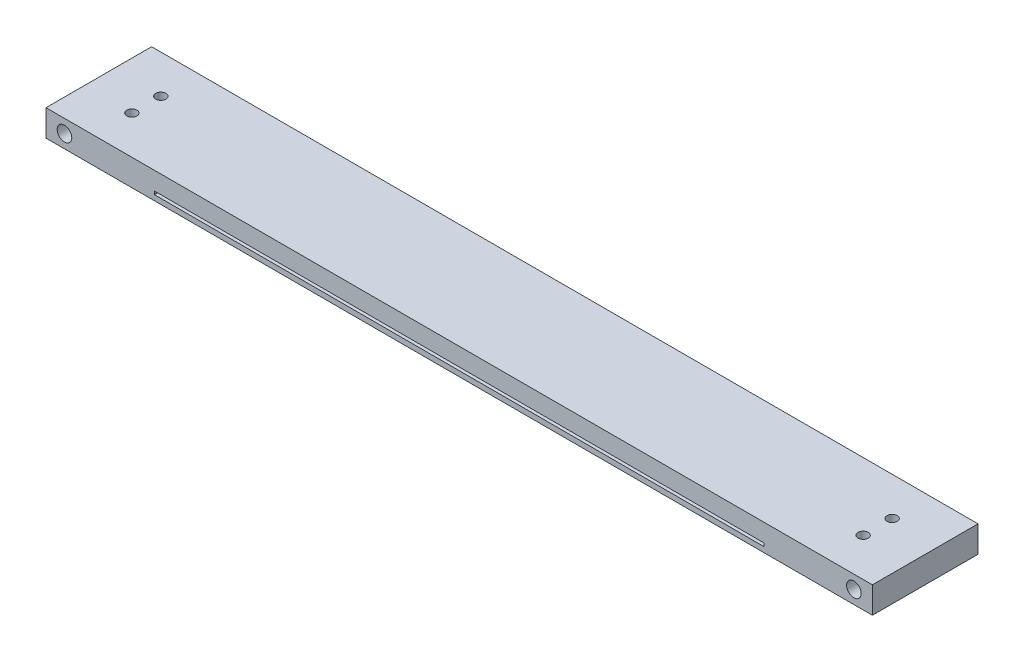
SolidWorks part; units mm, degrees
ref_plane "Front Plane" through (0, 0, 0) normal (0, 0, 1) x (1, 0, 0)
ref_plane "Top Plane" through (0, 0, 0) normal (0, 1, 0) x (1, 0, 0)
ref_plane "Right Plane" through (0, 0, 0) normal (1, 0, 0) x (0, 0, -1)
sketch "Sketch1" plane through (0, 0, 0) normal (1, 0, 0) x (0, 0, -1)
  line L1 (0, 0) -> (40, 0)
  line L2 (0, 0) -> (0, 10)
  line L3 (0, 10) -> (40, 10)
  line L4 (40, 0) -> (40, 10)
  dimension "D1" = 10
  dimension "D2" = 40
extrude "Boss-Extrude1" add sketch "Sketch1" along normal blind 312.998
sketch "Sketch2" plane through (0, 0, -40) normal (0, 0, -1) x (-1, 0, 0)
  line L1 (-271.949, 2) -> (-41.049, 2)
  line L2 (-271.949, 2) -> (-271.949, 3.2)
  line L3 (-271.949, 3.2) -> (-41.049, 3.2)
  line L4 (-41.049, 2) -> (-41.049, 3.2)
  line L5 (-271.949, 3.2) -> (-312.998, 0) construction
  line L6 (-41.049, 3.2) -> (0, 0) construction
  line L7 (-312.998, 0) -> (0, 0) construction
  dimension "D1" = 230.9
  dimension "D2" = 2
  dimension "D3" = 1.2
extrude "Cut-Extrude1" cut sketch "Sketch2" against normal through all
sketch "Sketch3" plane through (0, 10, 0) normal (0, 1, 0) x (1, 0, 0)
  line L0 (156.499, 71.4665) -> (156.499, -49.9307) construction
  line L1 (0, 40) -> (156.499, 71.4665) construction
  line L2 (156.499, 71.4665) -> (312.998, 40) construction
  line L3 (312.998, 40) -> (312.998, 0) construction
  line L4 (312.998, 40) -> (0, 40) construction
  line L5 (312.998, 40) -> (294.998, 25.5) construction
  line L6 (294.998, 25.5) -> (294.998, 14.5) construction
  line L7 (294.998, 14.5) -> (312.998, 0) construction
  circle A0 centre (294.998, 25.5) radius 1.9177
  circle A1 centre (294.998, 14.5) radius 1.9177
  circle A2 centre (18, 14.5) radius 1.9177
  circle A3 centre (18, 25.5) radius 1.9177
  dimension "D3" = 3.8354
  dimension "D1" = 18
  dimension "D2" = 14.5
extrude "Cut-Extrude2" cut sketch "Sketch3" against normal through all
sketch "Sketch4" plane through (0, 0, 0) normal (0, -1, 0) x (1, 0, 0)
  line L1 (14.5837, -12.5276) -> (14.5837, -16.4724)
  line L2 (14.5837, -16.4724) -> (18, -18.4448)
  line L3 (18, -18.4448) -> (21.4163, -16.4724)
  line L4 (21.4163, -16.4724) -> (21.4163, -12.5276)
  line L5 (21.4163, -12.5276) -> (18, -10.5552)
  line L6 (18, -10.5552) -> (14.5837, -12.5276)
  line L7 (14.5837, -23.5276) -> (14.5837, -27.4724)
  line L8 (14.5837, -27.4724) -> (18, -29.4448)
  line L9 (18, -29.4448) -> (21.4163, -27.4724)
  line L10 (21.4163, -27.4724) -> (21.4163, -23.5276)
  line L11 (21.4163, -23.5276) -> (18, -21.5552)
  line L12 (18, -21.5552) -> (14.5837, -23.5276)
  line L13 (298.4143, -12.5276) -> (294.998, -10.5552)
  line L14 (294.998, -10.5552) -> (291.5817, -12.5276)
  line L15 (291.5817, -12.5276) -> (291.5817, -16.4724)
  line L16 (291.5817, -16.4724) -> (294.998, -18.4448)
  line L17 (294.998, -18.4448) -> (298.4143, -16.4724)
  line L18 (298.4143, -16.4724) -> (298.4143, -12.5276)
  line L19 (291.5817, -23.5276) -> (291.5817, -27.4724)
  line L20 (291.5817, -27.4724) -> (294.998, -29.4448)
  line L21 (294.998, -29.4448) -> (298.4143, -27.4724)
  line L22 (298.4143, -27.4724) -> (298.4143, -23.5276)
  line L23 (298.4143, -23.5276) -> (294.998, -21.5552)
  line L24 (294.998, -21.5552) -> (291.5817, -23.5276)
  circle A0 centre (18, -14.5) radius 3.4163 construction
  circle A1 centre (18, -25.5) radius 3.4163 construction
  circle A2 centre (294.998, -14.5) radius 3.4163 construction
  circle A3 centre (294.998, -25.5) radius 3.4163 construction
  dimension "D1" = 6.8326
extrude "Cut-Extrude3" cut sketch "Sketch4" against normal blind 4.3
sketch "Sketch5" plane through (0, 0, 0) normal (0, 0, 1) x (1, 0, 0)
  line L0 (0, 10) -> (7, 5) construction
  line L1 (7, 5) -> (0, 0) construction
  line L2 (0, 10) -> (156.499, 87.0064) construction
  line L3 (156.499, 87.0064) -> (312.998, 10) construction
  line L4 (312.998, 10) -> (312.998, 0) construction
  line L5 (312.998, 10) -> (0, 10) construction
  line L6 (156.499, 87.0064) -> (156.499, -80.9825) construction
  line L7 (305.998, 5) -> (312.998, 0) construction
  line L8 (312.998, 10) -> (305.998, 5) construction
  circle A0 centre (7, 5) radius 2.7623
  circle A1 centre (305.998, 5) radius 2.7623
  dimension "D1" = 5.5245
  dimension "D2" = 7
extrude "Cut-Extrude4" cut sketch "Sketch5" against normal through all
sketch "Sketch6" plane through (0, 0, 0) normal (-1, 0, 0) x (0, 0, 1)
  line L0 (-40, 10) -> (-33, 8.4163) construction
  line L1 (-33, 8.4163) -> (-29.8453, 8.4163)
  line L2 (-33, 8.4163) -> (-33, 1.5837)
  line L3 (-33, 1.5837) -> (-29.8453, 1.5837)
  line L4 (-29.8453, 8.4163) -> (-29.8453, 1.5837)
  line L9 (-33, 1.5837) -> (-40, 0) construction
  line L10 (-40, 10) -> (-20, 18.9404) construction
  line L11 (-20, 18.9404) -> (0, 10) construction
  line L12 (-20, 18.9404) -> (-20, -7.3414) construction
  line L13 (-7, 1.5837) -> (0, 0) construction
  line L14 (0, 10) -> (-7, 8.4163) construction
  line L15 (-10.1547, 8.4163) -> (-10.1547, 1.5837)
  line L16 (-7, 1.5837) -> (-10.1547, 1.5837)
  line L17 (-7, 8.4163) -> (-7, 1.5837)
  line L18 (-7, 8.4163) -> (-10.1547, 8.4163)
  dimension "D1" = 7
  dimension "D2" = 3.1547
  dimension "D3" = 6.8326
extrude "Cut-Extrude5" cut sketch "Sketch6" against normal blind 15
ref_plane "Plane1" through (156.499, 0, 0) normal (-1, 0, 0) x (0, 0, 1)
